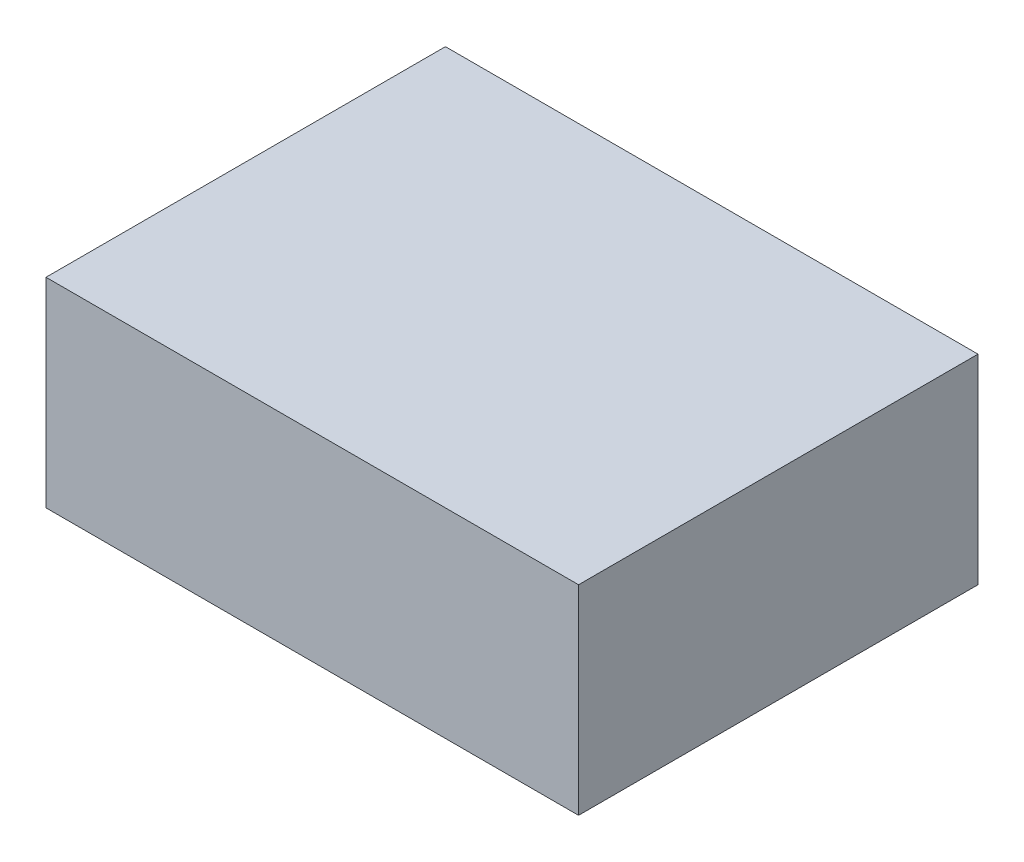
SolidWorks part; units mm, degrees
ref_plane "Front Plane" through (0, 0, 0) normal (0, 0, 1) x (1, 0, 0)
ref_plane "Top Plane" through (0, 0, 0) normal (0, 1, 0) x (1, 0, 0)
ref_plane "Right Plane" through (0, 0, 0) normal (1, 0, 0) x (0, 0, -1)
sketch "Sketch1" plane through (0, 0, 0) normal (0, 1, 0) x (1, 0, 0)
  line L1 (-50.8, 38.1) -> (50.8, 38.1)
  line L2 (-50.8, 38.1) -> (-50.8, -38.1)
  line L3 (-50.8, -38.1) -> (50.8, -38.1)
  line L4 (50.8, 38.1) -> (50.8, -38.1)
  dimension "D1" = 101.6
  dimension "D2" = 76.2
  dimension "D3" = 38.1
  dimension "D4" = 50.8
extrude "Boss-Extrude1" add sketch "Sketch1" along normal blind 38.1 contours L2 L3 L4 L1
